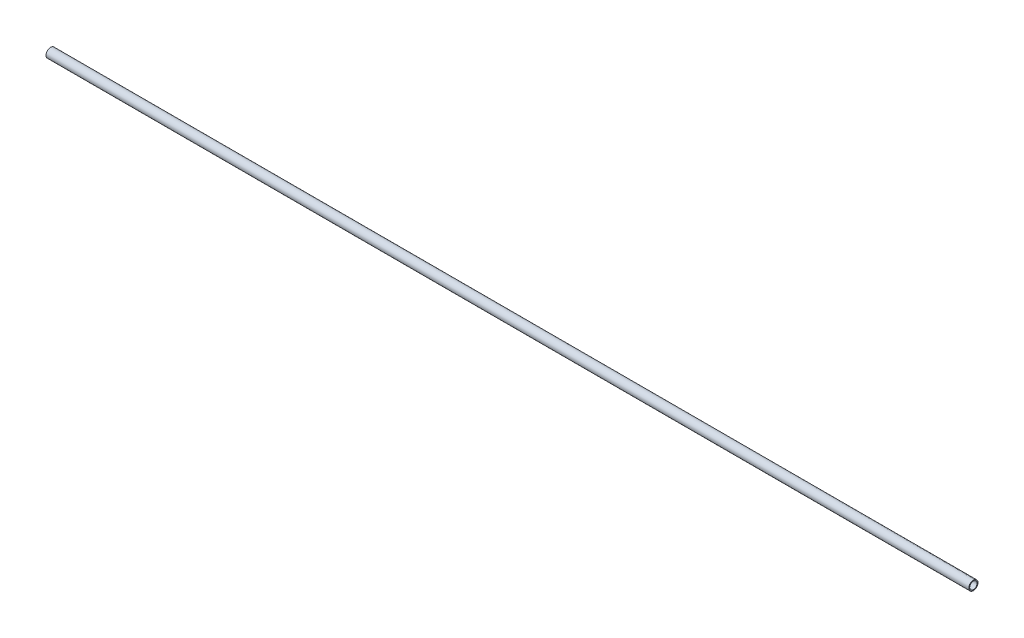
SolidWorks part; units mm, degrees
material "windcatcher"
ref_plane "Front Plane" through (0, 0, 0) normal (0, 0, 1) x (1, 0, 0)
ref_plane "Top Plane" through (0, 0, 0) normal (0, 1, 0) x (1, 0, 0)
ref_plane "Right Plane" through (0, 0, 0) normal (1, 0, 0) x (0, 0, -1)
sketch "Sketch1" plane through (0, 0, 0) normal (1, 0, 0) x (0, 0, -1)
  circle A0 centre (0, 0) radius 5
  circle A1 centre (0, 0) radius 4
  dimension "D1" = 10
  dimension "D2" = 8
extrude "Boss-Extrude1" add sketch "Sketch1" along normal mid plane 1000
